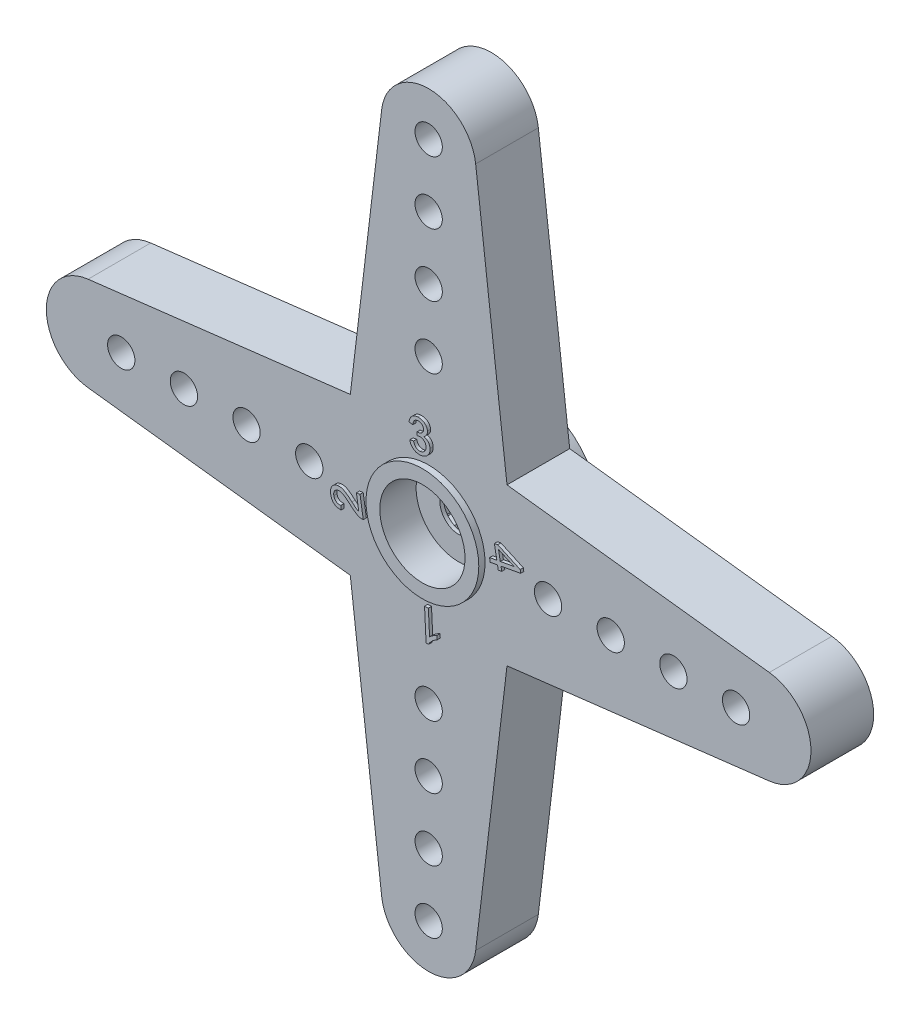
SolidWorks part; units mm, degrees
material "Nylon 101"
ref_plane "Front Plane" through (0, 0, 0) normal (0, 0, 1) x (1, 0, 0)
ref_plane "Top Plane" through (0, 0, 0) normal (0, 1, 0) x (1, 0, 0)
ref_plane "Right Plane" through (0, 0, 0) normal (1, 0, 0) x (0, 0, -1)
sketch "Sketch1" plane through (0, 0, 0) normal (0, 0, 1) x (1, 0, 0)
  line L0 (-3.75, -27.1714) -> (-6.25, -6.25)
  line L1 (-6.25, -6.25) -> (-27.1714, -3.75)
  line L2 (-27.1714, 3.75) -> (-6.25, 6.25)
  line L3 (-6.25, 6.25) -> (-3.75, 27.1714)
  line L4 (3.75, 27.1714) -> (6.25, 6.25)
  line L5 (6.25, 6.25) -> (27.1714, 3.75)
  line L6 (27.1714, -3.75) -> (6.25, -6.25)
  line L7 (6.25, -6.25) -> (3.75, -27.1714)
  line L8 (-6.25, 6.25) -> (6.25, 6.25) construction
  line L9 (6.25, 6.25) -> (6.25, -6.25) construction
  line L10 (6.25, -6.25) -> (-6.25, -6.25) construction
  line L11 (-6.25, 6.25) -> (-6.25, -6.25) construction
  line L12 (0, 0) -> (-6.25, 0) construction
  line L13 (0, 0) -> (0, -6.25) construction
  line L14 (-26.7233, 0) -> (-6.25, 0) construction
  line L15 (0, -26.7233) -> (0, -6.25) construction
  line L16 (26.7233, 0) -> (6.25, 0) construction
  line L17 (0, 6.25) -> (0, 26.7233) construction
  line L18 (-30.5, 0) -> (-26.7233, 0) construction
  line L19 (26.7233, 0) -> (30.5, 0) construction
  arc A0 (-27.1714, 3.75) -> (-27.1714, -3.75) centre (-26.7233, 0) ccw
  arc A1 (27.1714, 3.75) -> (27.1714, -3.75) centre (26.7233, 0) cw
  arc A2 (-3.75, 27.1714) -> (3.75, 27.1714) centre (0, 26.7233) cw
  arc A3 (3.75, -27.1714) -> (-3.75, -27.1714) centre (0, -26.7233) cw
  dimension "D1" = 61
  dimension "D2" = 12.5
  dimension "D3" = 7.5
extrude "Boss-Extrude1" add sketch "Sketch1" along normal blind 5
sketch "Sketch2" plane through (0, 0, 5) normal (0, 0, 1) x (1, 0, 0)
  circle A0 centre (0, 0) radius 1.5
  dimension "D1" = 3
extrude "Cut-Extrude1" cut sketch "Sketch2" against normal up to next
sketch "Sketch3" plane through (0, 0, 5) normal (0, 0, 1) x (1, 0, 0)
  circle A0 centre (0, 0) radius 3.4
  dimension "D1" = 6.8
extrude "Cut-Extrude2" cut sketch "Sketch3" against normal blind 2.4
sketch "Sketch4" plane through (0, 0, 5) normal (0, 0, 1) x (1, 0, 0)
  circle A0 centre (0, 0) radius 3.4 construction
  circle A1 centre (0, 0) radius 3.4
  circle A2 centre (0, 0) radius 4.5
  dimension "D1" = 9
extrude "Boss-Extrude2" add sketch "Sketch4" along normal blind 0.5
sketch "Sketch5" plane through (0, 0, 5) normal (0, 0, 1) x (1, 0, 0)
  line L0 (0, 27) -> (0, 22) construction
  line L1 (0, 22) -> (0, 17) construction
  line L2 (0, 17) -> (0, 12) construction
  line L3 (0, 12) -> (0, 0) construction
  circle A0 centre (0, 27) radius 1.09
  circle A1 centre (0, 22) radius 1.09
  circle A2 centre (0, 17) radius 1.09
  circle A3 centre (0, 12) radius 1.09
  dimension "D1" = 2.18
  dimension "D2" = 5
  dimension "D3" = 12
extrude "Cut-Extrude3" cut sketch "Sketch5" against normal up to next
pattern_circular "CirPattern1" count 2 over 360 about axis through (0, 0, 0) along (0, 0, 1) of "Cut-Extrude3"
sketch "Sketch6" plane through (0, 0, 0) normal (0, 0, -1) x (-1, 0, 0)
  circle A0 centre (0, 0) radius 6
  circle A1 centre (0, 0) radius 1.5 construction
  circle A2 centre (0, 0) radius 1.5
  dimension "D1" = 12
extrude "Boss-Extrude3" add sketch "Sketch6" along normal blind 2.7
sketch "Sketch7" plane through (0, 0, -2.7) normal (0, 0, -1) x (-1, 0, 0)
  circle A0 centre (0, 0) radius 3.75
  dimension "D1" = 7.5
extrude "Cut-Extrude4" cut sketch "Sketch7" against normal blind 5
sketch "Sketch8" plane through (0, 0, -2.7) normal (0, 0, -1) x (-1, 0, 0)
  line L0 (-0.7387, 3.6765) -> (0, 3.25)
  line L1 (0, 3.25) -> (0.7387, 3.6765)
  circle A0 centre (0, 0) radius 3.75 construction
  circle A1 centre (0, 0) radius 3.75 construction
  arc A2 (0.7387, 3.6765) -> (-0.7387, 3.6765) centre (0, 0) ccw
  circle A3 centre (0, 0) radius 3.25 construction
  dimension "D1" = 6.5
  dimension "D2" = 120
extrude "Boss-Extrude4" add sketch "Sketch8" against normal up to surface (5 mm away) up to face at (-3.75, 0, 2.3)
pattern_circular "CirPattern2" count 15 over 360 about axis through (0, 0, 0) along (0, 0, 1) of "Boss-Extrude4"
sketch "Sketch9" plane through (0, 0, 5) normal (0, 0, 1) x (1, 0, 0)
  line L1 (-5.25, -5.25) -> (5.25, -5.25) construction
  line L2 (-5.25, -5.25) -> (-5.25, 5.25) construction
  line L3 (-5.25, 5.25) -> (5.25, 5.25) construction
  line L4 (5.25, -5.25) -> (5.25, 5.25) construction
  line L5 (-5.25, -5.25) -> (5.25, 5.25) construction
  line L6 (-5.25, 5.25) -> (5.25, -5.25) construction
  circle A0 centre (0, 0) radius 5.25 construction
  text T0 "1      2       3      4"
  dimension "D1" = 10.5
extrude "Boss-Extrude5" add sketch "Sketch9" along normal blind 0.25
sketch "Sketch12" plane through (0, 0, 5) normal (0, 0, 1) x (1, 0, 0)
  line L0 (-24.525, 0) -> (-19.525, 0) construction
  line L1 (-19.525, 0) -> (-14.525, 0) construction
  line L2 (-14.525, 0) -> (-9.525, 0) construction
  line L3 (-9.525, 0) -> (0, 0) construction
  line L4 (0, 0) -> (9.525, 0) construction
  line L5 (9.525, 0) -> (14.525, 0) construction
  line L6 (14.525, 0) -> (19.525, 0) construction
  line L7 (19.525, 0) -> (24.525, 0) construction
  line L8 (0, 27) -> (0, 22) construction
  circle A0 centre (9.525, 0) radius 1.09
  circle A1 centre (-9.525, 0) radius 1.09
  circle A2 centre (14.525, 0) radius 1.09
  circle A3 centre (19.525, 0) radius 1.09
  circle A4 centre (24.525, 0) radius 1.09
  circle A5 centre (-14.525, 0) radius 1.09
  circle A6 centre (-19.525, 0) radius 1.09
  circle A7 centre (-24.525, 0) radius 1.09
  circle A8 centre (0, 12) radius 1.09 construction
  point P24 (9.525, 0)
  point P25 (-35.8504, 0)
  point P26 (24.525, 0)
  dimension "D1" = 19.05
extrude "Cut-Extrude7" cut sketch "Sketch12" against normal up to next
